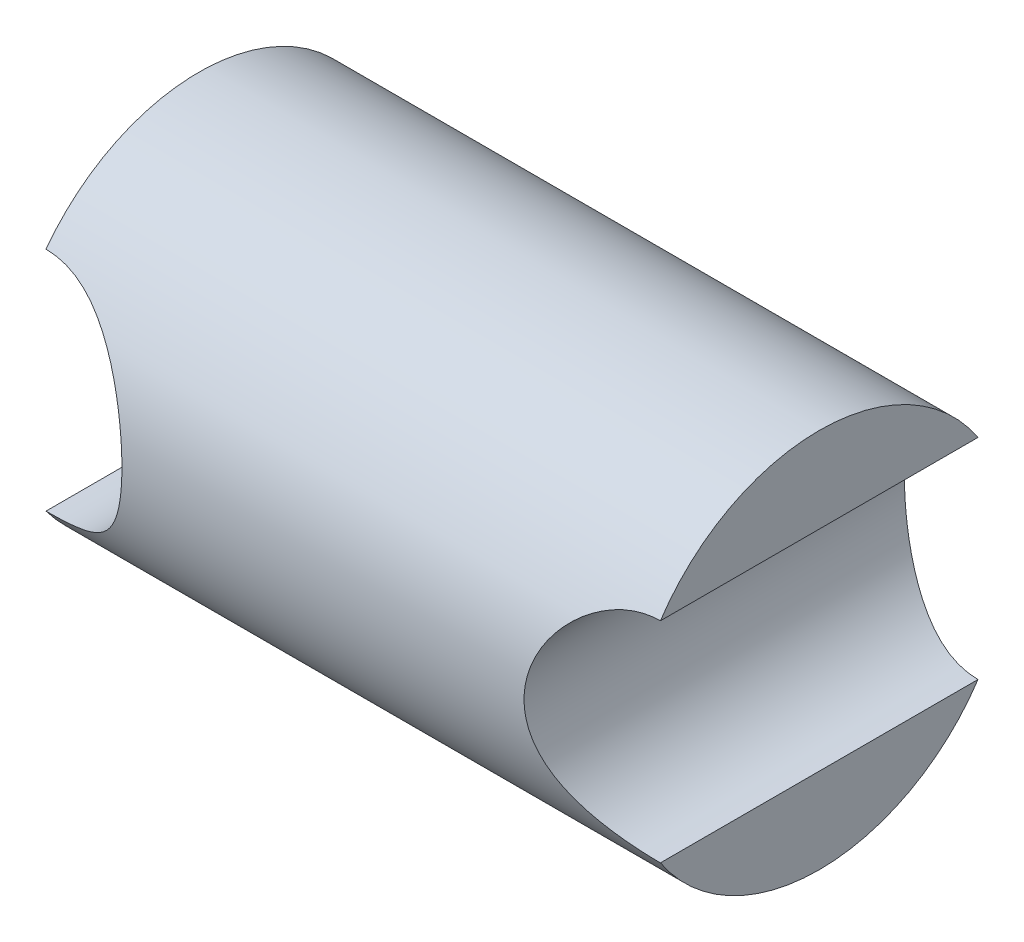
SolidWorks part; units mm, degrees
material "Legs"
ref_plane "Front Plane" through (0, 0, 0) normal (0, 0, 1) x (1, 0, 0)
ref_plane "Top Plane" through (0, 0, 0) normal (0, 1, 0) x (1, 0, 0)
ref_plane "Right Plane" through (0, 0, 0) normal (1, 0, 0) x (0, 0, -1)
sketch "Sketch1" plane through (0, 0, 0) normal (1, 0, 0) x (0, 0, -1)
  circle A0 centre (0, 0) radius 23
  dimension "D1" = 46
extrude "Boss-Extrude1" add sketch "Sketch1" along normal blind 75
sketch "Sketch2" plane through (0, 0, 0) normal (0, 0, 1) x (1, 0, 0)
  circle A0 centre (0, 0) radius 13.7099
  circle A1 centre (74.9821, 0) radius 12.6702
extrude "Cut-Extrude1" cut sketch "Sketch2" against normal up to next and the other way up to next
